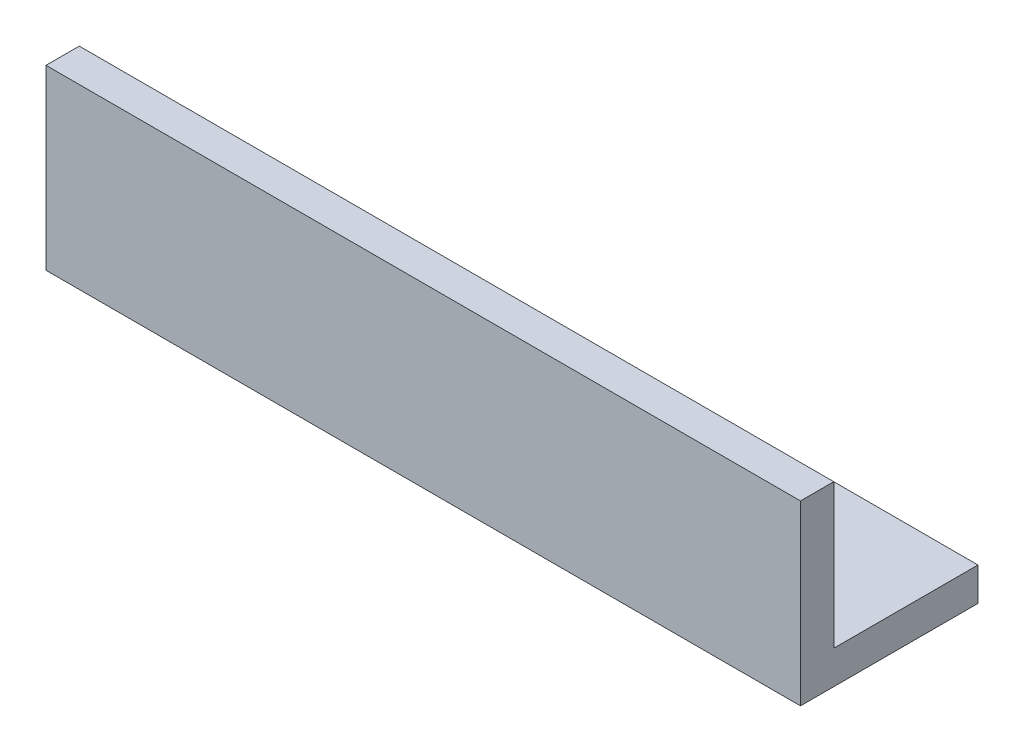
SolidWorks part; units mm, degrees
material "6061 Alloy"
ref_plane "Front Plane" through (0, 0, 0) normal (0, 0, 1) x (1, 0, 0)
ref_plane "Top Plane" through (0, 0, 0) normal (0, 1, 0) x (1, 0, 0)
ref_plane "Right Plane" through (0, 0, 0) normal (1, 0, 0) x (0, 0, -1)
sketch "Sketch1" plane through (0, 0, 0) normal (1, 0, 0) x (0, 0, -1)
  line L0 (0, 0) -> (0, -25.4)
  line L1 (0, -25.4) -> (25.4, -25.4)
  line L2 (25.4, -25.4) -> (25.4, -20.6375)
  line L3 (25.4, -20.6375) -> (4.7625, -20.6375)
  line L4 (4.7625, -20.6375) -> (4.7625, 0)
  line L5 (4.7625, 0) -> (0, 0)
  dimension "D1" = 4.7625
  dimension "D2" = 4.7625
  dimension "D3" = 25.4
  dimension "D4" = 25.4
extrude "Boss-Extrude1" add sketch "Sketch1" along normal blind 107.95
sketch "Sketch2" plane through (0, -20.6375, 0) normal (0, 1, 0) x (1, 0, 0)
  line L1 (0, 25.4) -> (0, 4.7625) construction
  line L2 (107.95, 0) -> (0, 0) construction
  circle A0 centre (9.525, 11.1125) radius 3.175
  circle A1 centre (19.05, 17.4625) radius 3.175
  dimension "D1" = 11.1125
  dimension "D2" = 17.4625
  dimension "D3" = 19.05
  dimension "D4" = 6.35
  dimension "D5" = 6.35
  dimension "D6" = 9.525
extrude "Cut-Extrude1" cut sketch "Sketch2" against normal up to next
sketch "Sketch3" plane through (0, -25.4, 0) normal (0, -1, 0) x (1, 0, 0)
  circle A0 centre (76.3322, -13.4704) radius 3.175 construction
  circle A1 centre (76.3322, -13.4704) radius 3.175
extrude "Cut-Extrude2" cut sketch "Sketch3" against normal up to next
